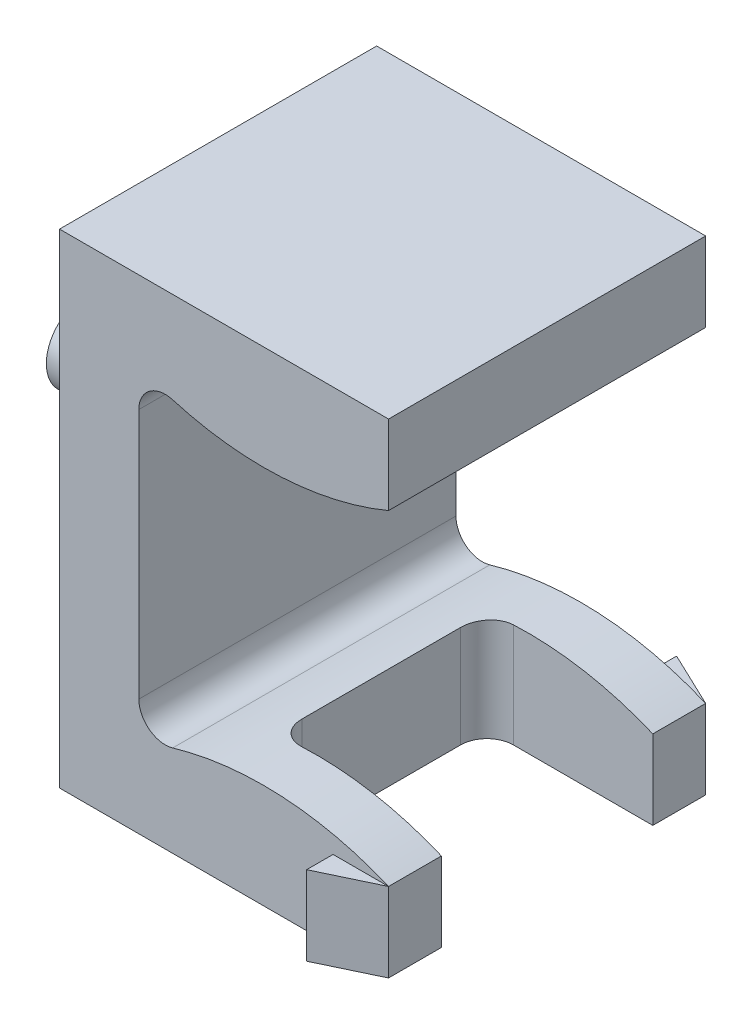
SolidWorks part; units mm, degrees
ref_plane "Front Plane" through (0, 0, 0) normal (0, 0, 1) x (1, 0, 0)
ref_plane "Top Plane" through (0, 0, 0) normal (0, 1, 0) x (1, 0, 0)
ref_plane "Right Plane" through (0, 0, 0) normal (1, 0, 0) x (0, 0, -1)
sketch "Sketch1" plane through (0, 0, 0) normal (0, 0, 1) x (1, 0, 0)
  line L2 (-159.7982, 9.1594) -> (-172.2482, 9.1594)
  line L3 (-172.2482, 9.1594) -> (-172.2482, -9.1594)
  line L7 (-169.2482, -22.8519) -> (-169.2482, 6.1594) construction
  line L12 (-169.2482, 5.1594) -> (-169.2482, 1.9844) construction
  line L13 (-142.8048, 5.1594) -> (-142.8048, -5.1594) construction
  line L15 (-156.5482, 5.1594) -> (21.2518, 5.1594) construction
  line L16 (-156.5482, -5.1594) -> (21.2518, -5.1594) construction
  line L23 (-159.7982, 6.1594) -> (-159.7982, 9.1594)
  line L28 (-164.5232, 5.2094) -> (-144.5007, 5.2094) construction
  line L29 (-156.5482, 5.1594) -> (-169.2482, 5.1594) construction
  line L30 (-169.2482, 6.1594) -> (-169.2482, 5.1594)
  line L34 (-169.2482, 5.1594) -> (-169.2482, -5.1594)
  line L35 (-172.2482, 0) -> (-169.2482, 0) construction
  line L36 (-169.2482, -6.1594) -> (-169.2482, -5.1594)
  line L37 (-159.7982, -6.1594) -> (-159.7982, -9.1594)
  line L38 (-159.7982, -9.1594) -> (-172.2482, -9.1594)
  line L39 (-159.7982, 5.1594) -> (-159.7982, 1.9844) construction
  arc A5 (-169.2482, 6.1594) -> (-159.7982, 6.1594) centre (-164.5232, 17.4347) ccw
  arc A6 (-169.2482, -6.1594) -> (-159.7982, -6.1594) centre (-164.5232, -17.4347) cw
  point P30 (-142.8048, 0)
  dimension "D4" = 3
  dimension "D3" = 3
  dimension "D1" = 0.05
  dimension "D2" = 1
extrude "MainBody" add sketch "Sketch1" along normal mid plane 12
sketch "Sketch3" plane through (0, -9.1594, 0) normal (0, -1, 0) x (1, 0, 0)
  line L0 (-159.7982, -6) -> (-161.8982, -7)
  line L1 (-161.8982, -7) -> (-161.8982, -6)
  line L2 (-172.2482, -6) -> (-159.7982, -6) construction
  line L3 (-161.8982, -6) -> (-159.7982, -6)
  line L4 (-162.8982, -12.7) -> (-162.8982, -6.35) construction
  line L5 (10.0753, 0) -> (-10.0753, 0) construction
  line L6 (-161.8982, 6) -> (-159.7982, 6)
  line L7 (-161.8982, 7) -> (-161.8982, 6)
  line L8 (-159.7982, 6) -> (-161.8982, 7)
  dimension "D1" = 1
  dimension "D2" = 1
extrude "Hook" add sketch "Sketch3" against normal up to vertex (3 mm away) up to point (-159.7982, -6.1594, -6)
sketch "Sketch4" plane through (0, -9.1594, 0) normal (0, -1, 0) x (1, 0, 0)
  line L0 (-159.7982, 6) -> (-159.7982, -6) construction
  line L1 (-159.7982, 4) -> (-166.0732, 4)
  line L2 (-159.7982, 4) -> (-159.7982, -4)
  line L3 (-159.7982, -4) -> (-166.0732, -4)
  line L4 (-166.0732, 4) -> (-166.0732, -4)
  line L5 (-172.2482, 6) -> (-172.2482, -6) construction
  line L6 (-172.2482, -6) -> (-161.8982, -6) construction
  line L7 (-162.8982, -6.35) -> (-169.2482, -6.35) construction
  point P6 (-166.0732, 0)
  point P9 (-172.2482, 0)
  point P14 (-166.0732, -6.35)
  dimension "D1" = 2
extrude "Flex" cut sketch "Sketch4" against normal up to next
fillet "Fillet1" radius 1 2 edges at (-166.0732, -7.2337, -4) (-166.0732, -7.2337, 4)
fillet "Fillet2" radius 1 2 edges at (-169.2482, 6.1594, 0) (-169.2482, -6.1594, 0)
sketch "Sketch5" [suppressed] plane through (-172.2482, 0, 0) normal (-1, 0, 0) x (0, 0, 1)
  line L1 (-6, 9.1594) -> (6, 9.1594)
  line L2 (-6, 9.1594) -> (-6, -9.1594)
  line L3 (-6, -9.1594) -> (6, -9.1594)
  line L4 (6, 9.1594) -> (6, -9.1594)
extrude "Boss-Extrude1" [suppressed] add sketch "Sketch5" along normal blind 15
sketch "Sketch6" [suppressed] plane through (0, 9.1594, 0) normal (0, 1, 0) x (1, 0, 0)
  line L0 (-187.2482, -6) -> (-187.2482, 6) construction
  circle A0 centre (-182.2482, 0) radius 3.302
  dimension "D1" = 6.604
  dimension "D2" = 5
extrude "Cut-Extrude2" [suppressed] cut sketch "Sketch6" against normal through all
sketch "Sketch7" plane through (-172.2482, 0, 0) normal (-1, 0, 0) x (0, 0, 1)
  circle A0 centre (0, 0) radius 1.5
  dimension "D1" = 3
extrude "Boss-Extrude2" add sketch "Sketch7" along normal blind 5
fillet "Fillet3" radius 1 1 edges at (-172.2482, 0, -1.5)
equation "\"HookThickness\"= 3mm"
equation "\"D3@Sketch1\"=\"HookThickness\""
equation "\"D4@Sketch1\"=\"HookThickness\""
equation "\"CylinderDiameter\"=3"
equation "\"D1@Sketch7\"=\"CylinderDiameter\""
